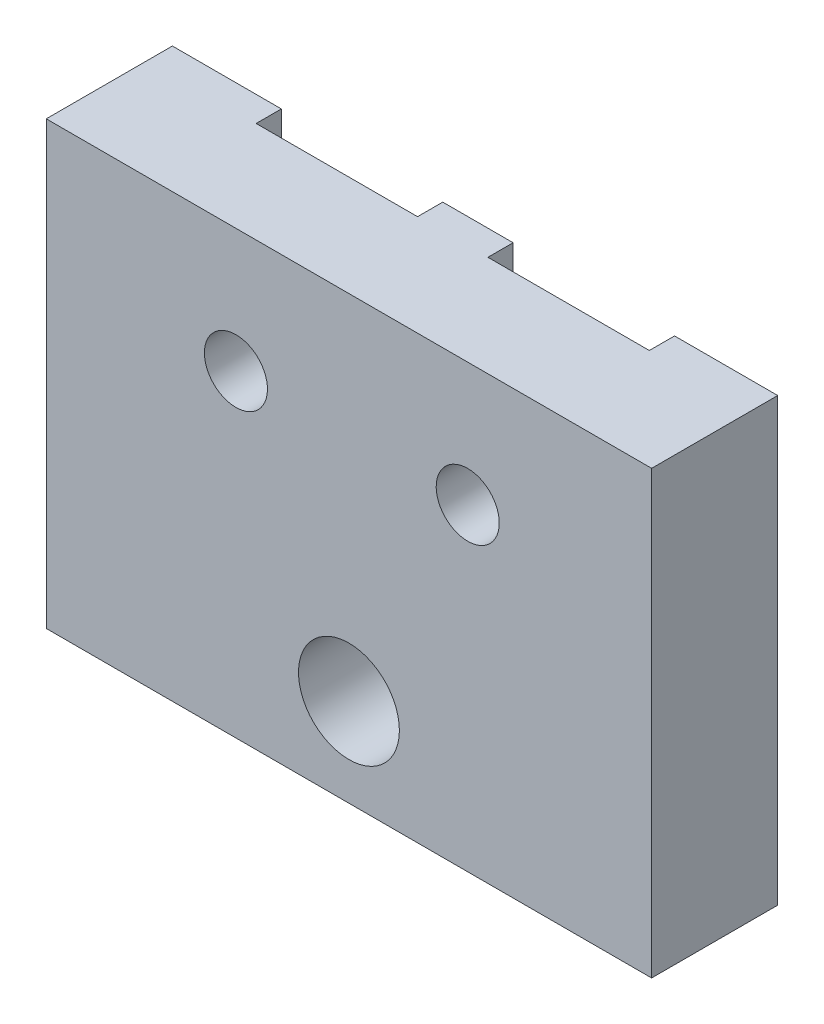
SolidWorks part; units mm, degrees
material "Alliage 1060"
ref_plane "Plan de face" through (0, 0, 0) normal (0, 0, 1) x (1, 0, 0)
ref_plane "Plan de dessus" through (0, 0, 0) normal (0, 1, 0) x (1, 0, 0)
ref_plane "Plan de droite" through (0, 0, 0) normal (1, 0, 0) x (0, 0, -1)
sketch "Esquisse1" plane through (0, 0, 0) normal (0, 0, 1) x (1, 0, 0)
  line L1 (-12, -3.5) -> (12, -3.5)
  line L2 (-12, -3.5) -> (-12, 14)
  line L3 (-12, 14) -> (12, 14)
  line L4 (12, -3.5) -> (12, 14)
  line L5 (-12, 3.5) -> (-12, -3.5) construction
  circle A0 centre (0, 0) radius 2
  dimension "D3" = 4
  dimension "D4" = 17.5
extrude "Extrusion1" add sketch "Esquisse1" along normal blind 5
sketch "Esquisse3" plane through (0, 0, 0) normal (0, 0, 1) x (1, 0, 0)
  line L6 (-7.6802, 24.5) -> (-1.2802, 24.5)
  line L7 (-7.6802, 9.1) -> (-7.6802, 24.5)
  line L8 (-1.2802, 24.5) -> (-1.2802, 9.1)
  line L12 (1.5091, 9.1) -> (1.5091, 24.5)
  line L13 (7.9091, 24.5) -> (7.9091, 9.1)
  line L14 (1.5091, 24.5) -> (7.9091, 24.5)
  arc A1 (-7.6802, 9.1) -> (-1.2802, 9.1) centre (-4.4802, 9.1) ccw
  arc A3 (1.5091, 9.1) -> (7.9091, 9.1) centre (4.7091, 9.1) ccw
extrude "Enlèv. mat.-Extru.2" cut sketch "Esquisse3" along normal up to surface (1 mm away)
hole_wizard "Trou taraudé M3x0.51" positions "Esquisse5" profile "Esquisse4" tap size "M3x0.5" standard "ISO" end condition through all
sketch "Esquisse5" plane through (-4.3496, 3.5439, 1) normal (0, 0, -1) x (-1, 0, 0)
  point P0 (0.1307, 5.5561)
  point P1 (-9.0587, 5.5561)
sketch "Esquisse4" plane through (-4.4802, 9.1, 1) normal (1, 0, 0) x (0, 1, 0)
  line L0 (0, 0) -> (0, 4)
  line L1 (0, 4) -> (1.25, 4)
  line L2 (1.25, 4) -> (1.25, 0)
  line L5 (1.25, 0) -> (0, 0)
  line L11 (0, -6.35) -> (0, 107.95) construction
  dimension "Diamètre du trou pour taraudage jusqu'au prochain" = 2.5
  dimension "Profondeur du trou pour taraudage jusqu'au prochain" = 4
cosmetic thread "Filetage de perçage1" parameters "D2"=3
cosmetic thread "Filetage de perçage2" parameters "D2"=3
